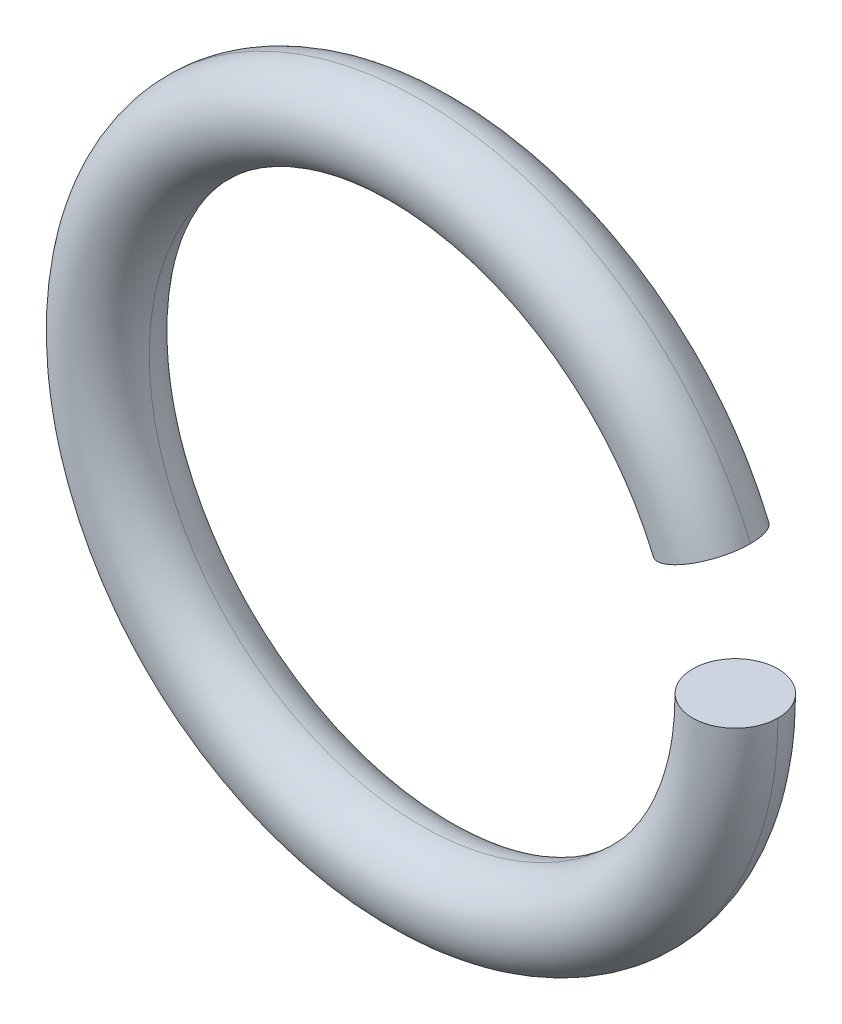
SolidWorks part; units mm, degrees
ref_plane "Front" through (0, 0, 0) normal (0, 0, 1) x (1, 0, 0)
ref_plane "Top" through (0, 0, 0) normal (0, 1, 0) x (1, 0, 0)
ref_plane "Right" through (0, 0, 0) normal (1, 0, 0) x (0, 0, -1)
sketch "Sketch1" plane through (0, 0, 0) normal (0, 0, 1) x (1, 0, 0)
  line L0 (-76.5339, 0) -> (24.9274, 0) construction
  line L1 (0, 65.6634) -> (0, -53.6178) construction
  line L2 (0, 0) -> (3.9134, 1.6302) construction
  arc A0 (2.3539, 0.9806) -> (2.55, 0) centre (0, 0) ccw
  dimension "d2" = 5.1
  dimension "e" = 1
sketch "Sketch2" plane through (0, 0, 0) normal (0, 1, 0) x (1, 0, 0)
  circle A0 centre (2.95, 0) radius 0.4
  point P2 (2.55, 0)
  dimension "d4" = 0.8
sweep "Sweep1" add profiles "Sketch2" path "Sketch1"
split line "Split Line3"
